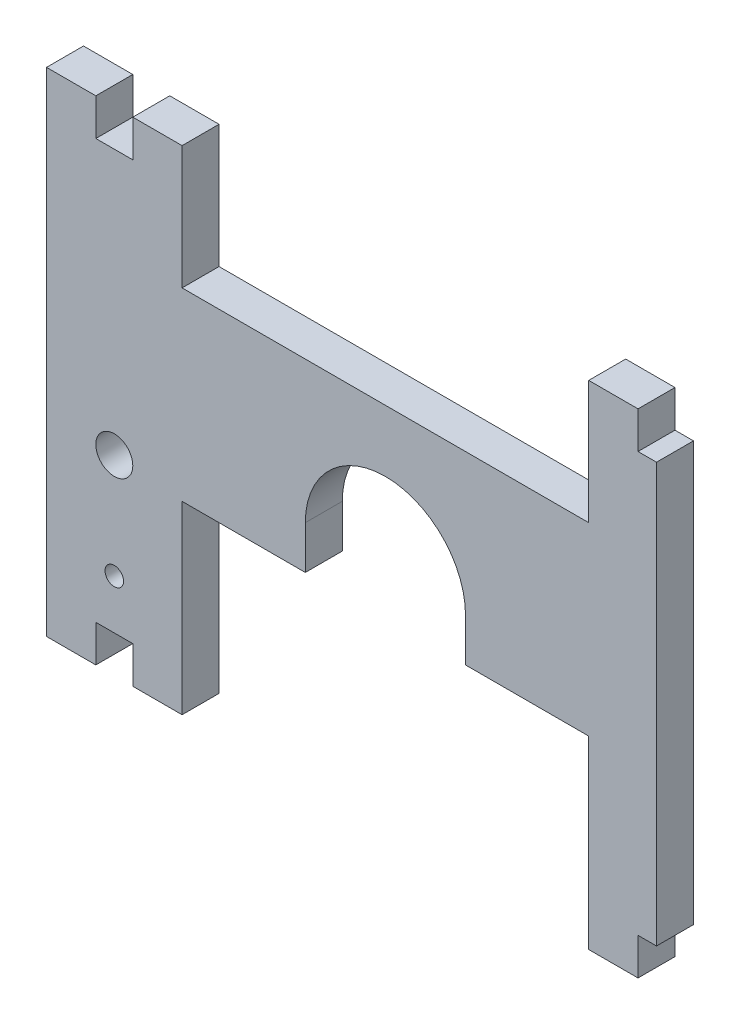
SolidWorks part; units mm, degrees
ref_plane "Plan de face" through (0, 0, 0) normal (0, 0, 1) x (1, 0, 0)
ref_plane "Plan de dessus" through (0, 0, 0) normal (0, 1, 0) x (1, 0, 0)
ref_plane "Plan de droite" through (0, 0, 0) normal (1, 0, 0) x (0, 0, -1)
sketch "Esquisse1" plane through (0, 0, 0) normal (0, 0, 1) x (1, 0, 0)
  line L0 (-14, 80) -> (-14, 74)
  line L1 (0, 0) -> (-22, 0)
  line L2 (0, 0) -> (0, 80)
  line L3 (0, 80) -> (-22, 80)
  line L4 (-22, 0) -> (-22, 80)
  line L5 (-14, 74) -> (-8, 74)
  line L6 (-8, 74) -> (-8, 80)
  line L7 (-14, 0) -> (-14, 6)
  line L8 (-14, 6) -> (-8, 6)
  line L9 (-8, 6) -> (-8, 0)
  line L10 (0, 60) -> (66, 60)
  line L11 (66, 60) -> (66, 30)
  line L12 (66, 30) -> (0, 30)
  line L13 (0, 30) -> (0, 60)
  line L14 (66, 80) -> (66, 0)
  line L15 (66, 0) -> (88, 0)
  line L16 (88, 0) -> (88, 80)
  line L17 (88, 80) -> (66, 80)
  line L18 (74, 80) -> (74, 74)
  line L19 (74, 74) -> (80, 74)
  line L20 (80, 74) -> (80, 80)
  line L21 (74, 0) -> (74, 6)
  line L22 (74, 6) -> (80, 6)
  line L23 (80, 6) -> (80, 0)
  line L24 (20, 37) -> (20, 30)
  line L25 (46, 37) -> (46, 30)
  circle A0 centre (33, 37) radius 13
  dimension "D6" = 66
  dimension "D16" = 26
  dimension "D1" = 80
  dimension "D2" = 22
  dimension "D3" = 8
  dimension "D4" = 8
  dimension "D5" = 6
  dimension "D7" = 22
  dimension "D8" = 8
  dimension "D9" = 8
  dimension "D10" = 6
  dimension "D11" = 8
  dimension "D12" = 6
  dimension "D13" = 8
  dimension "D14" = 30
  dimension "D15" = 30
  dimension "D17" = 33
  dimension "D18" = 7
extrude "Boss.-Extru.1" add sketch "Esquisse1" along normal blind 6 contours L8 L9 L1 L2 L3 L6 L5 L0 L4 L7 | L12 L11 L10 L2 | L22 L23 L15 L16 L17 L20 L19 L18 L14 L11 L21
sketch "Esquisse2" plane through (0, 0, 6) normal (0, 0, 1) x (1, 0, 0)
  line L0 (-22, 0) -> (-22, 80) construction
  line L1 (-14, 0) -> (-22, 0) construction
  line L2 (-14, 6) -> (-8, 6) construction
  circle A0 centre (-11, 31) radius 3
  circle A1 centre (-11, 14) radius 1.5
  dimension "D1" = 6
  dimension "D4" = 3
  dimension "D2" = 11
  dimension "D3" = 31
  dimension "D5" = 8
extrude "Enlèv. mat.-Extru.1" cut sketch "Esquisse2" against normal blind 30 contours A0 | A1
sketch "Esquisse4" plane through (0, 0, 0) normal (0, 0, -1) x (-1, 0, 0)
  line L0 (-72.4992, 44.7491) -> (-74.4526, 50.4222)
  line L1 (-72.4992, 44.7491) -> (-64.935, 47.3537)
  line L2 (-74.4526, 50.4222) -> (-66.8884, 53.0268)
  line L3 (-64.935, 47.3537) -> (-66.8884, 53.0268)
  line L4 (-61.2153, 54.9802) -> (-53.6512, 57.5847)
  line L5 (-61.2153, 54.9802) -> (-59.2619, 49.3071)
  line L6 (-53.6512, 57.5847) -> (-51.6977, 51.9116)
  line L7 (-59.2619, 49.3071) -> (-51.6977, 51.9116)
extrude "Enlèv. mat.-Extru.2" [suppressed] cut sketch "Esquisse4" against normal blind 10
sketch "Esquisse5" plane through (0, 0, 6) normal (0, 0, 1) x (1, 0, 0)
  line L0 (77, 74) -> (77, 6)
  line L1 (74, 74) -> (80, 74) construction
  line L2 (74, 6) -> (80, 6) construction
  line L3 (77, 6) -> (80, 6)
  line L4 (80, 6) -> (80, 0)
  line L5 (80, 0) -> (88, 0)
  line L6 (88, 0) -> (88, 80)
  line L7 (88, 80) -> (80, 80) construction
  line L8 (88, 0) -> (88, 80) construction
  line L9 (88, 80) -> (80, 80)
  line L10 (80, 80) -> (80, 74)
  line L11 (80, 74) -> (77, 74)
extrude "Enlèv. mat.-Extru.3" cut sketch "Esquisse5" against normal blind 10
